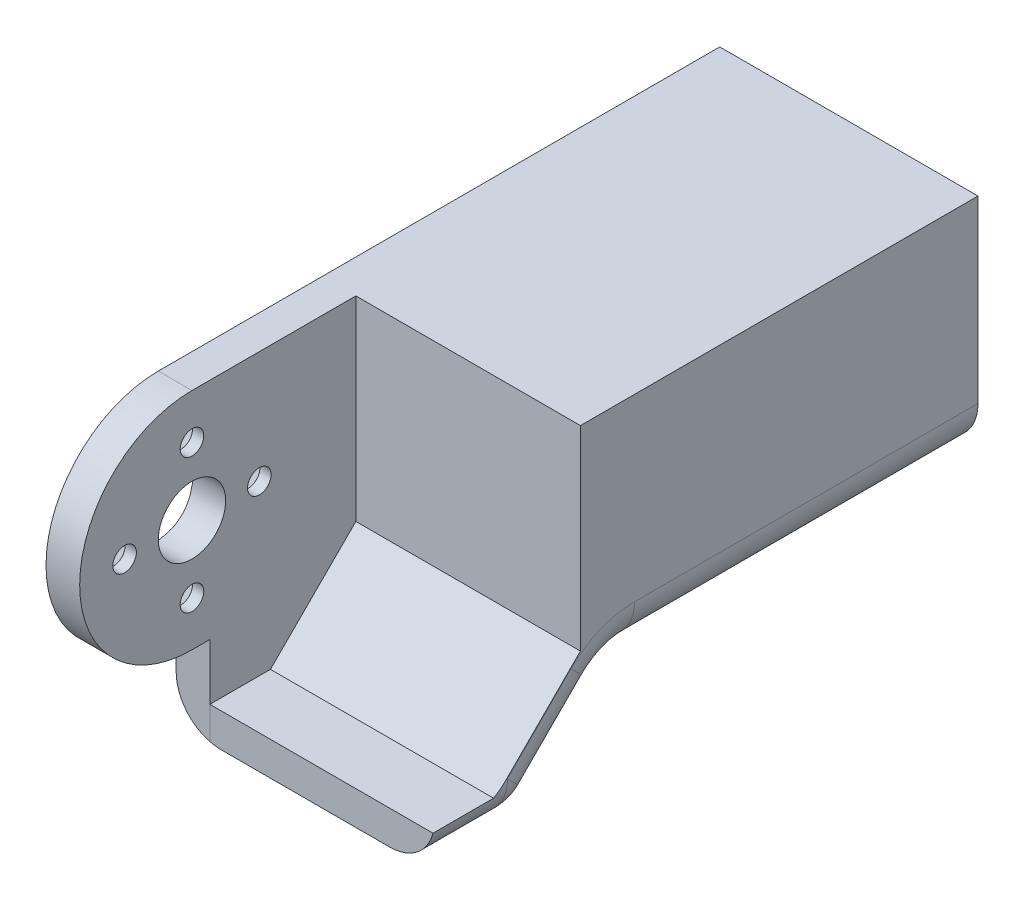
SolidWorks part; units mm, degrees
ref_plane "Front Plane" through (0, 0, 0) normal (0, 0, 1) x (1, 0, 0)
ref_plane "Top Plane" through (0, 0, 0) normal (0, 1, 0) x (1, 0, 0)
ref_plane "Right Plane" through (0, 0, 0) normal (1, 0, 0) x (0, 0, -1)
ref_plane "Plane1" through (15.5373, 0, 0) normal (1, 0, 0) x (0, 0, -1)
sketch "Sketch1" plane through (15.5373, 0, 0) normal (1, 0, 0) x (0, 0, -1)
  line L0 (-71.227, 229.327) -> (-119.6342, 229.327)
  line L1 (-119.6342, 229.327) -> (-119.6342, 201.327)
  line L2 (-119.6342, 201.327) -> (-71.227, 201.327)
  line L3 (-71.227, 201.327) -> (-71.227, 229.327)
extrude "Boss-Extrude1" add sketch "Sketch1" against normal blind 20
sketch "Sketch2" plane through (-4.4627, 0, 0) normal (-1, 0, 0) x (0, 0, 1)
  line L0 (71.227, 201.327) -> (71.227, 229.327)
  line L1 (71.227, 229.327) -> (121.227, 229.327)
  line L2 (121.227, 209.327) -> (119.6342, 209.327)
  line L3 (119.6342, 209.327) -> (119.6342, 201.327)
  line L4 (119.6342, 201.327) -> (71.227, 201.327)
  arc A0 (121.227, 229.327) -> (121.227, 209.327) centre (121.227, 219.327) cw
extrude "Boss-Extrude2" add sketch "Sketch2" along normal blind 3
sketch "Sketch3" plane through (15.5373, 0, 0) normal (1, 0, 0) x (0, 0, -1)
  line L0 (-106.6342, 211.9327) -> (-106.6342, 229.327)
  line L1 (-106.6342, 229.327) -> (-119.6342, 229.327)
  line L2 (-119.6342, 229.327) -> (-119.6342, 204.327)
  line L3 (-119.6342, 204.327) -> (-114.2399, 204.327)
  line L4 (-114.2399, 204.327) -> (-106.6342, 211.9327)
extrude "Cut-Extrude1" cut sketch "Sketch3" against normal blind 20
sketch "Sketch4" plane through (-7.4627, 0, 0) normal (-1, 0, 0) x (0, 0, 1)
  line L0 (71.227, 201.327) -> (111.4682, 201.327)
  line L1 (111.4682, 201.327) -> (103.4682, 209.327)
  line L2 (103.4682, 209.327) -> (71.227, 209.327)
  line L3 (71.227, 209.327) -> (71.227, 201.327)
extrude "Cut-Extrude2" cut sketch "Sketch4" against normal through all
hole_wizard "Ø6.0 (6) Diameter Hole1" positions "Sketch6" profile "Sketch5" hole size "Ø6.0" standard "ANSI Metric"
sketch "Sketch6" plane through (-4.4627, 0, 0) normal (1, 0, 0) x (0, 0, -1)
  point P0 (-121.227, 219.327)
sketch "Sketch5" plane through (-4.4627, 219.327, 121.227) normal (0, 1, 0) x (0, 0, -1)
  line L0 (0, 0) -> (0, 3)
  line L1 (0, 3) -> (3, 3)
  line L2 (3, 3) -> (3, 0)
  line L5 (3, 0) -> (0, 0)
  line L11 (0, -6.35) -> (0, 107.95) construction
  dimension "Thru Hole Dia." = 6
  dimension "Thru Hole Depth" = 3
hole_wizard "Ø2.1 (2.1) Diameter Hole1" positions "Sketch8" profile "Sketch7" hole size "Ø2.1" standard "ANSI Metric"
sketch "Sketch8" plane through (-7.4627, 0, 0) normal (-1, 0, 0) x (0, 0, 1)
  point P0 (121.227, 225.327)
  point P1 (127.227, 219.327)
  point P2 (121.227, 213.327)
  point P3 (115.227, 219.327)
sketch "Sketch7" plane through (-7.4627, 225.327, 121.227) normal (0, 1, 0) x (0, 0, 1)
  line L0 (0, 0) -> (0, 23)
  line L1 (0, 23) -> (1.05, 23)
  line L2 (1.05, 23) -> (1.05, 2)
  line L3 (1.05, 2) -> (3.05, 0)
  line L5 (3.05, 0) -> (0, 0)
  line L6 (-1.05, 2) -> (-3.05, 0) construction
  line L11 (0, -6.35) -> (0, 107.95) construction
  dimension "Thru Hole Dia." = 2.1
  dimension "Thru Hole Depth" = 23
  dimension "Near C'Sink Dia." = 6.1
  dimension "Near C'Sink Angle" = 90
fillet "Fillet1" radius 4 8 edges at (15.5373, 201.327, 115.5512) (15.5373, 209.327, 87.3476) (15.5373, 205.327, 107.4682) (-7.4627, 201.327, 115.5512) (4.0373, 201.327, 111.4682) (-7.4627, 205.327, 107.4682) (-7.4627, 209.327, 87.3476) (4.0373, 209.327, 103.4682)
